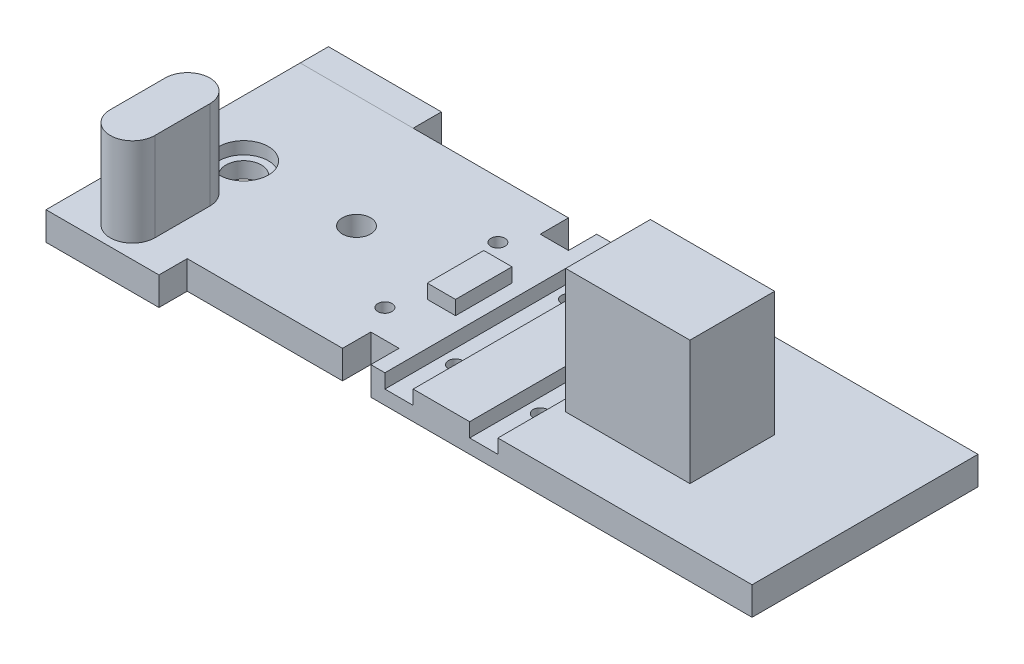
SolidWorks part; units mm, degrees
ref_plane "Front Plane" through (0, 0, 0) normal (0, 0, 1) x (1, 0, 0)
ref_plane "Top Plane" through (0, 0, 0) normal (0, 1, 0) x (1, 0, 0)
ref_plane "Right Plane" through (0, 0, 0) normal (1, 0, 0) x (0, 0, -1)
sketch "Sketch1" plane through (0, 0, 0) normal (0, 1, 0) x (1, 0, 0)
  line L1 (0, 0) -> (304.8, 0)
  line L2 (0, 0) -> (0, 101.6)
  line L3 (0, 101.6) -> (304.8, 101.6)
  line L4 (304.8, 0) -> (304.8, 101.6)
  dimension "D1" = 304.8
  dimension "4" = 101.6
extrude "Boss-Extrude1" add sketch "Sketch1" along normal blind 12.7
sketch "Sketch3" plane through (0, 12.7, 0) normal (0, 1, 0) x (1, 0, 0)
  line L0 (0, 101.6) -> (0, 0) construction
  line L1 (304.8, 101.6) -> (0, 101.6) construction
  circle A0 centre (25.4, 50.8) radius 11.1125
  dimension "D1" = 25.4
  dimension "D3" = 22.225
  dimension "D2" = 50.8
extrude "Cut-Extrude2" cut sketch "Sketch3" against normal blind 5.5562
sketch "Sketch9" plane through (0, 0, 0) normal (0, 0, 1) x (1, 0, 0)
  line L1 (0, 12.7) -> (0, 0) construction
  line L9 (165.1, 25.4) -> (165.1, 0)
  line L10 (0, 0) -> (304.8, 0) construction
  line L19 (0, 12.7) -> (304.8, 12.7) construction
  line L20 (139.7, 12.7) -> (152.4, 12.7)
  line L21 (139.7, 12.7) -> (139.7, 6.35)
  line L22 (139.7, 6.35) -> (152.4, 6.35)
  line L23 (152.4, 12.7) -> (152.4, 6.35)
  line L24 (190.5, 6.35) -> (177.8, 6.35)
  line L25 (177.8, 12.7) -> (177.8, 6.35)
  line L26 (190.5, 12.7) -> (177.8, 12.7)
  line L27 (190.5, 12.7) -> (190.5, 6.35)
  line M17 (304.8, 12.7) -> (0, 12.7)
  dimension "D1" = 12.7
  dimension "D2" = 12.7
  dimension "D3" = 139.7
  dimension "0.25" = 6.35
extrude "Cut-Extrude5" cut sketch "Sketch9" against normal through all contours L23 L21 L22 M17 | L27 L25 L24 M17
sketch "Sketch15" plane through (0, 6.35, 0) normal (0, 1, 0) x (1, 0, 0)
  line L0 (139.7, 101.6) -> (139.7, 0) construction
  line L3 (177.8, 101.6) -> (177.8, 0) construction
  circle A0 centre (146.05, 25.4) radius 3.175
  circle A1 centre (184.15, 76.2) radius 3.175
  circle A2 centre (184.15, 25.4) radius 3.175
  circle A5 centre (146.05, 76.2) radius 3.175
  circle A6 centre (114.3, 25.4) radius 3.175
  circle A7 centre (114.3, 76.2) radius 3.175
  dimension "D1" = 31.75
  dimension "D7" = 50.8
  dimension "D2" = 31.75
  dimension "D4" = 6.35
  dimension "D5" = 6.35
  dimension "D6" = 6.35
  dimension "D8" = 50.8
  dimension "D9" = 6.35
extrude "Cut-Extrude8" cut sketch "Sketch15" against normal blind 25.4 from surface at 6.35 starting at face at (25.4, 12.7, -39.6875)
sketch "Sketch17" plane through (0, 12.7, 0) normal (0, 1, 0) x (1, 0, 0)
  line L0 (190.5, 0) -> (304.8, 0) construction
  line L1 (195.58, 63.5) -> (251.46, 63.5)
  line L2 (195.58, 63.5) -> (195.58, 25.4)
  line L3 (195.58, 25.4) -> (251.46, 25.4)
  line L4 (251.46, 63.5) -> (251.46, 25.4)
  line L5 (190.5, 101.6) -> (190.5, 0) construction
  dimension "D1" = 38.1
  dimension "D2" = 55.88
  dimension "D3" = 25.4
  dimension "D4" = 5.08
extrude "Boss-Extrude5" add sketch "Sketch17" along normal blind 55.88
sketch "Sketch20" plane through (0, 0, 0) normal (-1, 0, 0) x (0, 0, 1)
  line L1 (0, 12.7) -> (12.7, 12.7)
  line L2 (0, 12.7) -> (0, 0)
  line L3 (0, 0) -> (12.7, 0)
  line L4 (12.7, 12.7) -> (12.7, 0)
  line L5 (-101.6, 12.7) -> (-114.3, 12.7)
  line L6 (-101.6, 12.7) -> (-101.6, 0)
  line L7 (-101.6, 0) -> (-114.3, 0)
  line L8 (-114.3, 12.7) -> (-114.3, 0)
  dimension "D1" = 12.7
  dimension "D2" = 12.7
extrude "Boss-Extrude7" add sketch "Sketch20" against normal blind 50.8 separate body
sketch "Sketch21" plane through (0, 7.1437, 0) normal (0, 1, 0) x (1, 0, 0)
  circle A0 centre (25.4, 50.8) radius 7.9375
  dimension "D1" = 15.875
extrude "Cut-Extrude10" cut sketch "Sketch21" against normal through all
sketch "Sketch22" plane through (0, 12.7, 0) normal (0, 1, 0) x (1, 0, 0)
  line L0 (25.4, 25.527) -> (25.4, 0.8077) construction
  line L1 (35.433, 25.527) -> (35.433, 0.8077)
  line L2 (15.367, 25.527) -> (15.367, 0.8077)
  arc A0 (35.433, 25.527) -> (15.367, 25.527) centre (25.4, 25.527) ccw
  arc A1 (15.367, 0.8077) -> (35.433, 0.8077) centre (25.4, 0.8077) ccw
  circle A2 centre (25.4, 50.8) radius 11.1125 construction
  point P3 (25.4, 13.1674)
  point P8 (25.4, 35.56)
  point P11 (25.4, -9.2253)
  dimension "D1" = 15.24
  dimension "D2" = 44.7853
  dimension "D3" = 20.066
extrude "Boss-Extrude8" add sketch "Sketch22" along normal blind 39.878
sketch "Sketch23" plane through (0, 12.7, 0) normal (0, 1, 0) x (1, 0, 0)
  line L0 (50.8, 0) -> (139.7, 0) construction
  circle A0 centre (76.1171, 50.8) radius 6.35
  dimension "D1" = 50.8
extrude "Cut-Extrude11" cut sketch "Sketch23" against normal through all
sketch "Sketch24" plane through (0, 12.7, 0) normal (0, 1, 0) x (1, 0, 0)
  line L1 (120.65, 63.5) -> (133.35, 63.5)
  line L2 (120.65, 63.5) -> (120.65, 38.1)
  line L3 (120.65, 38.1) -> (133.35, 38.1)
  line L4 (133.35, 63.5) -> (133.35, 38.1)
  circle A0 centre (114.3, 25.4) radius 3.175 construction
  dimension "D1" = 25.4
  dimension "D2" = 12.7
  dimension "D3" = 12.7
  dimension "D4" = 6.35
extrude "Boss-Extrude9" add sketch "Sketch24" along normal blind 6.35
sketch "Sketch25" plane through (0, 12.7, 0) normal (0, 1, 0) x (1, 0, 0)
  line L0 (139.7, 101.6) -> (0, 101.6) construction
  line L1 (120.65, 101.6) -> (133.35, 101.6)
  line L2 (120.65, 101.6) -> (120.65, 88.9)
  line L3 (120.65, 88.9) -> (133.35, 88.9)
  line L4 (133.35, 101.6) -> (133.35, 88.9)
  line L5 (50.8, 0) -> (139.7, 0) construction
  line L6 (120.65, 0) -> (133.35, 0)
  line L7 (120.65, 0) -> (120.65, 12.7)
  line L8 (120.65, 12.7) -> (133.35, 12.7)
  line L9 (133.35, 0) -> (133.35, 12.7)
  line L10 (120.65, 63.5) -> (120.65, 38.1) construction
  line L11 (120.65, 63.5) -> (120.65, 38.1) construction
  dimension "D1" = 0
  dimension "D2" = 0
  dimension "D3" = 12.7
  dimension "D4" = 12.7
  dimension "D5" = 12.7
  dimension "D6" = 12.7
extrude "Cut-Extrude12" cut sketch "Sketch25" against normal through all
